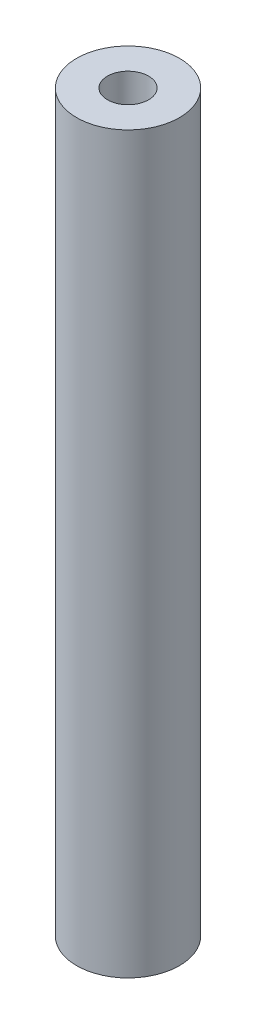
SolidWorks part; units mm, degrees
ref_plane "Front Plane" through (0, 0, 0) normal (0, 0, 1) x (1, 0, 0)
ref_plane "Top Plane" through (0, 0, 0) normal (0, 1, 0) x (1, 0, 0)
ref_plane "Right Plane" through (0, 0, 0) normal (1, 0, 0) x (0, 0, -1)
sketch "Sketch1" plane through (0, 0, 0) normal (0, 1, 0) x (1, 0, 0)
  circle A0 centre (0, 0) radius 1
  circle A1 centre (0, 0) radius 2.5
  dimension "D1" = 2
  dimension "D2" = 1.5
extrude "Boss-Extrude1" add sketch "Sketch1" along normal blind 35.7
